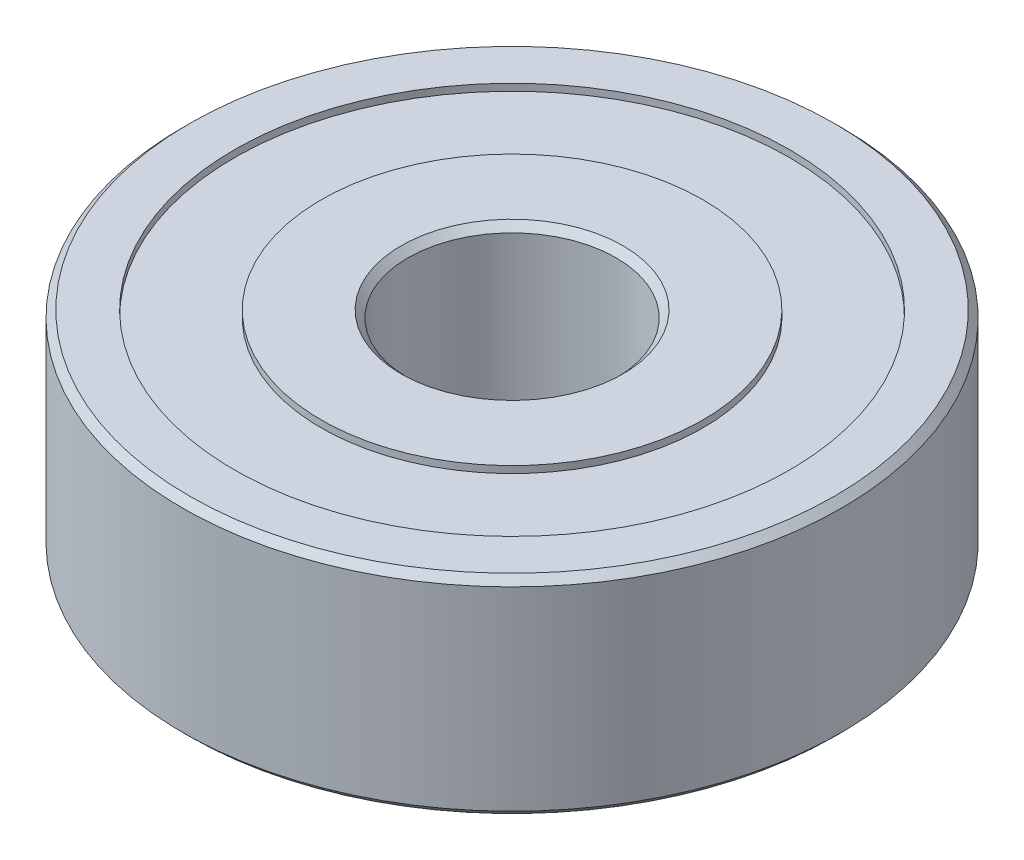
SolidWorks part; units mm, degrees
ref_plane "Front Plane" through (0, 0, 0) normal (0, 0, 1) x (1, 0, 0)
ref_plane "Top Plane" through (0, 0, 0) normal (0, 1, 0) x (1, 0, 0)
ref_plane "Right Plane" through (0, 0, 0) normal (1, 0, 0) x (0, 0, -1)
sketch "Sketch1" plane through (0, 0, 0) normal (0, 0, 1) x (1, 0, 0)
  line L0 (9.5, 5.8) -> (9.3, 6)
  line L1 (9.3, 6) -> (8, 6)
  line L2 (8, 6) -> (8, 5.8)
  line L3 (8, 5.8) -> (5.5, 5.8)
  line L4 (5.5, 5.8) -> (5.5, 6)
  line L5 (5.5, 6) -> (3.2, 6)
  line L6 (3.2, 6) -> (3, 5.8)
  line L7 (3, 5.8) -> (3, 0.2)
  line L8 (3, 0.2) -> (3.2, 0)
  line L9 (3.2, 0) -> (5.5, 0)
  line L10 (5.5, 0) -> (5.5, 0.2)
  line L11 (5.5, 0.2) -> (8, 0.2)
  line L12 (8, 0.2) -> (8, 0)
  line L13 (8, 0) -> (9.3, 0)
  line L14 (9.3, 0) -> (9.5, 0.2)
  line L15 (9.5, 0.2) -> (9.5, 5.8)
  line L16 (0, 6) -> (0, 0) construction
revolve "Revolve1" add sketch "Sketch1" angle 360 about L16
